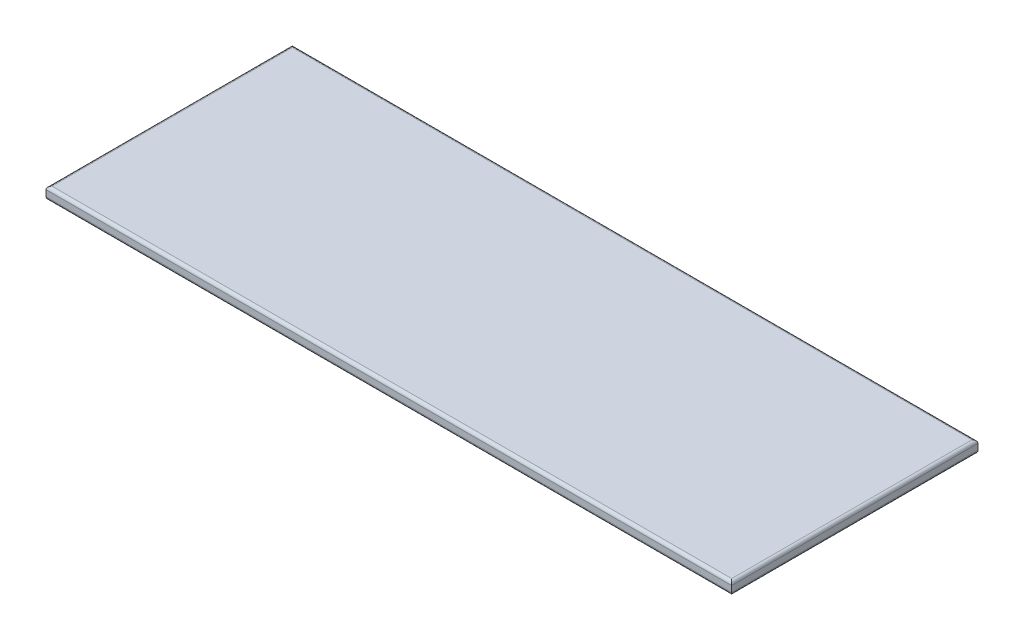
SolidWorks part; units mm, degrees
material "Copper"
ref_plane "Front Plane" through (0, 0, 0) normal (0, 0, 1) x (1, 0, 0)
ref_plane "Top Plane" through (0, 0, 0) normal (0, 1, 0) x (1, 0, 0)
ref_plane "Right Plane" through (0, 0, 0) normal (1, 0, 0) x (0, 0, -1)
sketch "Sketch1" plane through (0, 0, 0) normal (0, 1, 0) x (1, 0, 0)
  line L1 (0, 0) -> (113, 0)
  line L2 (0, 0) -> (0, 40.6)
  line L3 (0, 40.6) -> (113, 40.6)
  line L4 (113, 0) -> (113, 40.6)
extrude "Boss-Extrude1" add sketch "Sketch1" along normal blind 2
fillet "Fillet1" radius 0.5 8 edges at (56.5, 2, -40.6) (113, 2, -20.3) (56.5, 2, 0) (0, 2, -20.3) (56.5, 0, 0) (113, 0, -20.3) (56.5, 0, -40.6) (0, 0, -20.3)
ref_plane "Plane1" through (56.5, 0, 0) normal (-1, 0, 0) x (0, 0, 1)
ref_plane "Plane2" through (0, 0, -20.3) normal (0, 0, -1) x (-1, 0, 0)
ref_plane "Plane3" through (84.75, 0, 0) normal (-1, 0, 0) x (0, 0, 1)
ref_plane "Plane4" through (28.25, 0, 0) normal (-1, 0, 0) x (0, 0, 1)
